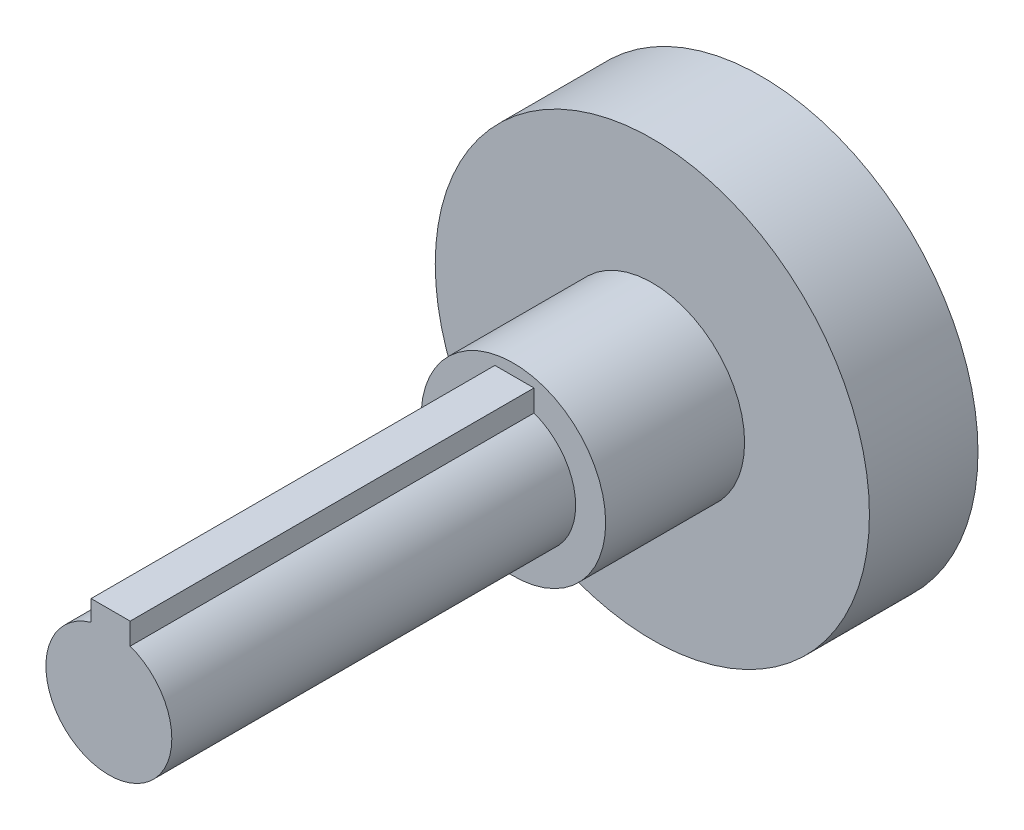
SolidWorks part; units mm, degrees
ref_plane "Front Plane" through (0, 0, 0) normal (1, 0, 0) x (0, 1, 0)
ref_plane "Top Plane" through (0, 0, 0) normal (0, 0, 1) x (0, 1, 0)
ref_plane "Right Plane" through (0, 0, 0) normal (0, 1, 0) x (-1, 0, 0)
sketch "Sketch1" plane through (0, 0, 0) normal (0, 0, 1) x (0, 1, 0)
  circle A0 centre (0, 0) radius 10
  dimension "D1" = 20
extrude "Boss-Extrude1" add sketch "Sketch1" along normal blind 5
sketch "Sketch3" plane through (0, 0, 5) normal (0, 0, 1) x (1, 0, 0)
  circle A0 centre (0, 0) radius 4.25
  dimension "D1" = 8.5
extrude "Boss-Extrude3" add sketch "Sketch3" along normal blind 6.4
sketch "Sketch2" plane through (0, 0, 11.4) normal (0, 0, 1) x (1, 0, 0)
  line L1 (-0.8511, 3.7289) -> (0.9489, 3.7289)
  line L2 (-0.8511, 3.7289) -> (-0.8511, 2.7821)
  line L4 (0.9489, 3.7289) -> (0.9489, 2.7289)
  arc A0 (-0.8511, 2.7821) -> (0.9489, 2.7289) centre (-0.0325, 0) ccw
  dimension "D1" = 5.8
  dimension "D3" = 0
  dimension "D2" = 1.8
  dimension "D4" = 1
extrude "Boss-Extrude2" add sketch "Sketch2" along normal blind 18.6
